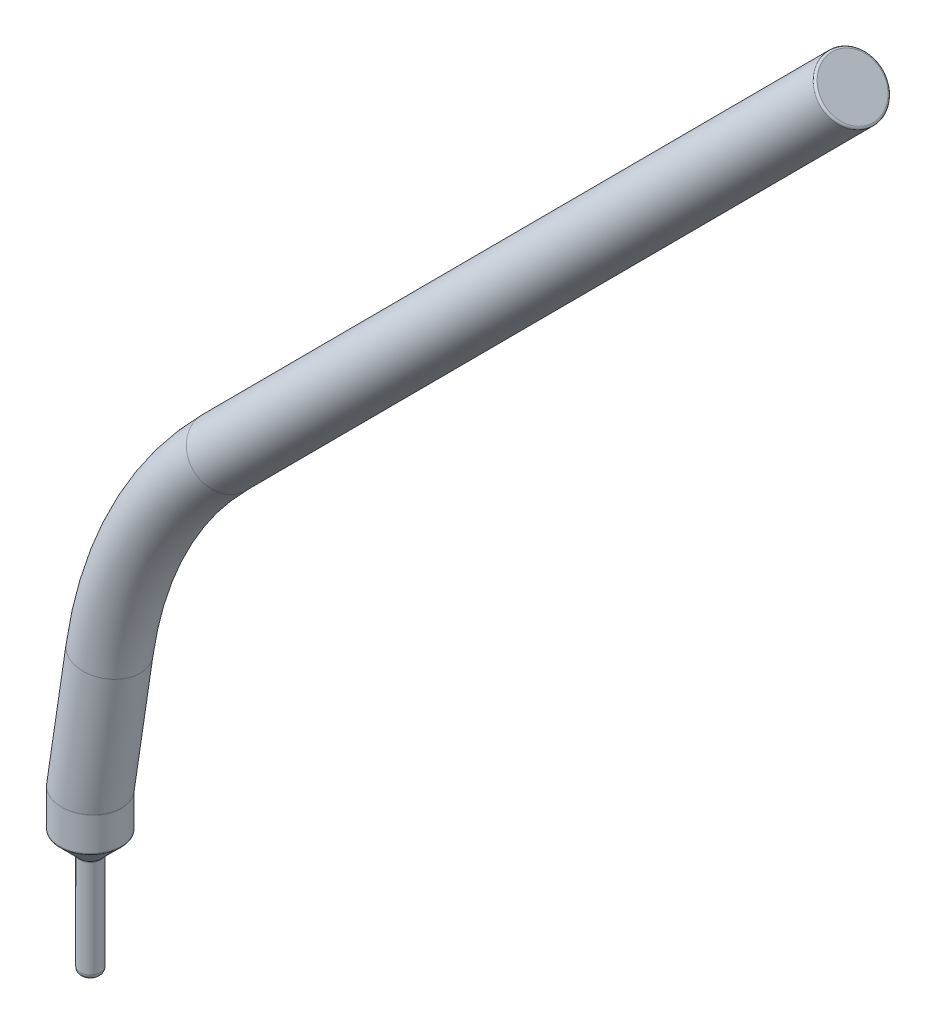
SolidWorks part; units mm, degrees
ref_plane "Front Plane" through (0, 0, 0) normal (0, 0, 1) x (1, 0, 0)
ref_plane "Top Plane" through (0, 0, 0) normal (0, 1, 0) x (1, 0, 0)
ref_plane "Right Plane" through (0, 0, 0) normal (1, 0, 0) x (0, 0, -1)
sketch "Sketch1" plane through (0, 0, 0) normal (0, 1, 0) x (1, 0, 0)
  line L0 (-1.65, 0) -> (1.65, 0) construction
  circle A0 centre (0, 0) radius 1.5
  dimension "D1" = 3
sketch "Sketch2" plane through (0, 0, 0) normal (0, 0, 1) x (1, 0, 0)
  line L0 (0, 0) -> (0, 1.7361)
  line L1 (0, 1.7361) -> (0.9254, 7.9646)
  line L2 (6.4833, 19.0282) -> (36.8874, 49.5444)
  arc A0 (0.9254, 7.9646) -> (6.4833, 19.0282) centre (20.5078, 5.0552) cw
sweep "Sweep1" add profiles "Sketch1" path "Sketch2"
ref_plane "Plane1" through (0, -1, 0) normal (0, -1, 0) x (-1, 0, 0)
sketch "Sketch3" plane through (0, -1, 0) normal (0, -1, 0) x (-1, 0, 0)
  circle A0 centre (0, 0) radius 0.5
  dimension "D1" = 1
extrude "Boss-Extrude1" add sketch "Sketch3" along normal blind 5 separate body
loft "Loft1" add section face at (0, 0, 1.5) section face at (0, -1, -0.5)
fillet "Fillet3" radius 0.25 1 edges at (0, -6, -0.5)
fillet "Fillet4" radius 0.1 3 edges at (36.8874, 49.5444, 1.5) (-1.5, 1.8469, 0) (0, 0, 1.5)
fillet "Fillet5" radius 0.1 1 edges at (0, -1, -0.5)
